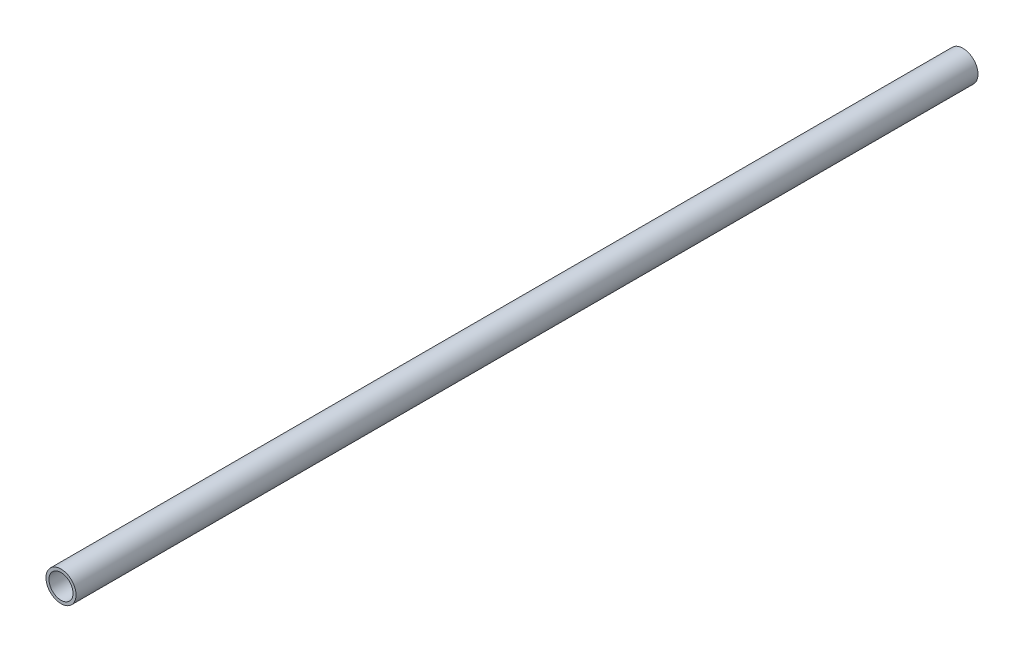
SolidWorks part; units mm, degrees
ref_plane "Front Plane" through (0, 0, 0) normal (0, 0, 1) x (1, 0, 0)
ref_plane "Top Plane" through (0, 0, 0) normal (0, 1, 0) x (1, 0, 0)
ref_plane "Right Plane" through (0, 0, 0) normal (1, 0, 0) x (0, 0, -1)
sketch "Sketch1" plane through (0, 0, 0) normal (0, 0, 1) x (1, 0, 0)
  circle A0 centre (0, 0) radius 5
  circle A1 centre (0, 0) radius 4
extrude "Boss-Extrude1" add sketch "Sketch1" along normal blind 300
